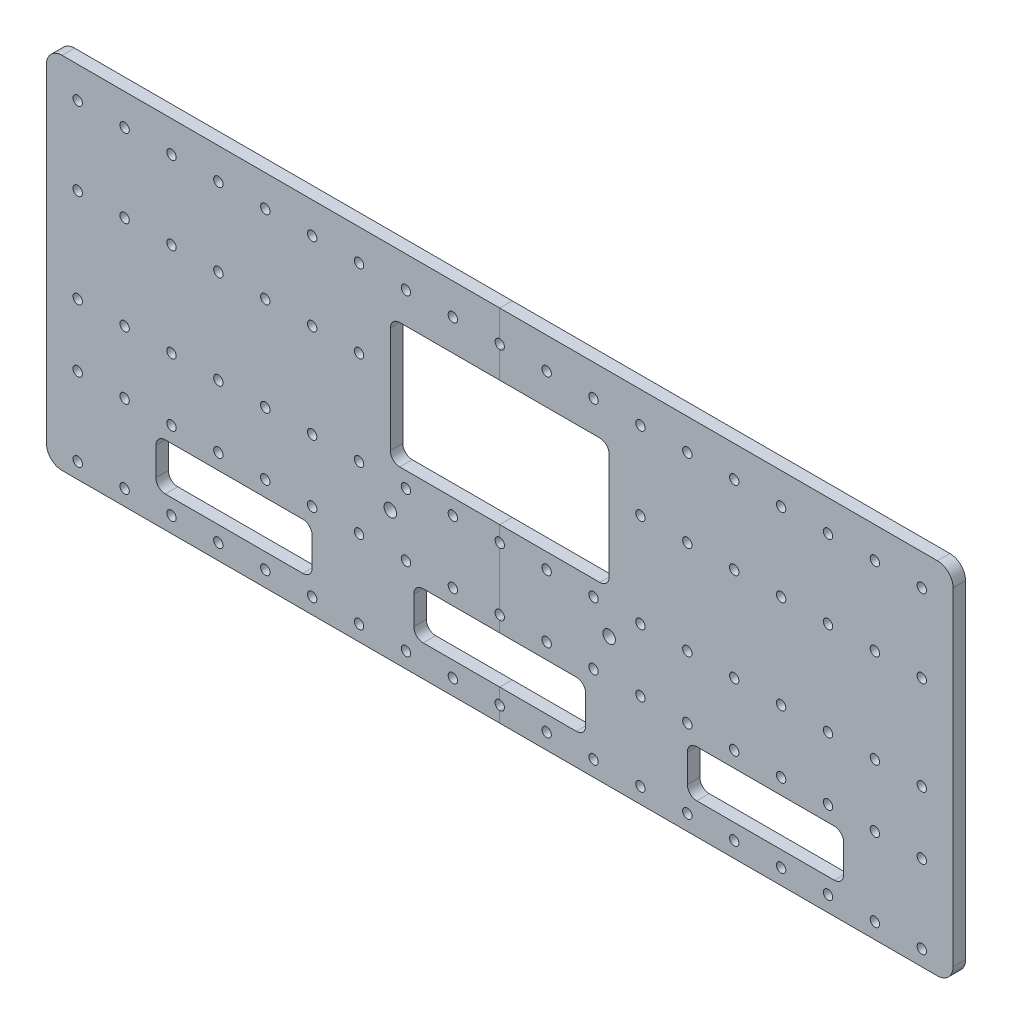
SolidWorks part; units mm, degrees
ref_plane "前视基准面" through (0, 0, 0) normal (0, 0, 1) x (1, 0, 0)
ref_plane "上视基准面" through (0, 0, 0) normal (0, 1, 0) x (1, 0, 0)
ref_plane "右视基准面" through (0, 0, 0) normal (1, 0, 0) x (0, 0, -1)
other "Configuration Table"
sketch "草图1" plane through (0, 0, 0) normal (0, 0, 1) x (1, 0, 0)
  line L1 (-145, 57.5) -> (145, 57.5)
  line L2 (-145, 57.5) -> (-145, -57.5)
  line L3 (-145, -57.5) -> (145, -57.5)
  line L4 (145, 57.5) -> (145, -57.5)
  line L5 (-145, 57.5) -> (145, -57.5) construction
  line L6 (-145, -57.5) -> (145, 57.5) construction
  point P0 (0, 0)
  dimension "D1" = 290
  dimension "D2" = 115
extrude "凸台-拉伸1" add sketch "草图1" along normal blind 4
sketch "草图2" plane through (0, 0, 4) normal (0, 0, 1) x (1, 0, 0)
  line L0 (-145, 47.5) -> (49855, 47.5) construction
  line L1 (-145, -57.5) -> (145, -57.5) construction
  line L2 (-145, -40) -> (49855, -40) construction
  line L3 (-145, 57.5) -> (-145, -57.5) construction
  line L4 (0, 0) -> (0, -50000) construction
  line L5 (145, 57.5) -> (-145, 57.5) construction
  line L6 (-135, 47.5) -> (-120, 47.5) construction
  line L7 (-135, -27.5) -> (-120, -27.5) construction
  circle A1 centre (-135, 47.5) radius 1.5
  circle A2 centre (-120, 47.5) radius 1.5
  circle A3 centre (-105, 47.5) radius 1.5
  circle A4 centre (-90, 47.5) radius 1.5
  circle A5 centre (-75, 47.5) radius 1.5
  circle A6 centre (-60, 47.5) radius 1.5
  circle A7 centre (-45, 47.5) radius 1.5
  circle A8 centre (-30, 47.5) radius 1.5
  circle A9 centre (-15, 47.5) radius 1.5
  circle A10 centre (0, 47.5) radius 1.5
  circle A11 centre (15, 47.5) radius 1.5
  circle A12 centre (30, 47.5) radius 1.5
  circle A13 centre (45, 47.5) radius 1.5
  circle A14 centre (60, 47.5) radius 1.5
  circle A15 centre (75, 47.5) radius 1.5
  circle A16 centre (90, 47.5) radius 1.5
  circle A17 centre (105, 47.5) radius 1.5
  circle A18 centre (120, 47.5) radius 1.5
  circle A19 centre (135, 47.5) radius 1.5
  circle A21 centre (150, 47.5) radius 1.5 [skipped]
  circle A22 centre (-135, -27.5) radius 1.5
  circle A23 centre (-120, -27.5) radius 1.5
  circle A24 centre (-105, -27.5) radius 1.5
  circle A25 centre (-90, -27.5) radius 1.5
  circle A26 centre (-75, -27.5) radius 1.5
  circle A27 centre (-60, -27.5) radius 1.5
  circle A28 centre (-45, -27.5) radius 1.5
  circle A29 centre (-30, -27.5) radius 1.5
  circle A30 centre (-15, -27.5) radius 1.5
  circle A31 centre (0, -27.5) radius 1.5
  circle A32 centre (15, -27.5) radius 1.5
  circle A33 centre (30, -27.5) radius 1.5
  circle A34 centre (45, -27.5) radius 1.5
  circle A35 centre (60, -27.5) radius 1.5
  circle A36 centre (75, -27.5) radius 1.5
  circle A37 centre (90, -27.5) radius 1.5
  circle A38 centre (105, -27.5) radius 1.5
  circle A39 centre (120, -27.5) radius 1.5
  circle A40 centre (135, -27.5) radius 1.5
  circle A50 centre (150, -27.5) radius 1.5 [skipped]
  circle A51 centre (165, -27.5) radius 1.5 [skipped]
  circle A52 centre (180, -27.5) radius 1.5 [skipped]
  circle A53 centre (195, -27.5) radius 1.5 [skipped]
  circle A54 centre (210, -27.5) radius 1.5 [skipped]
  circle A55 centre (225, -27.5) radius 1.5 [skipped]
  circle A56 centre (240, -27.5) radius 1.5 [skipped]
  circle A57 centre (255, -27.5) radius 1.5 [skipped]
  circle A58 centre (270, -27.5) radius 1.5 [skipped]
  circle A59 centre (135, -52.5) radius 1.5
  circle A60 centre (120, -52.5) radius 1.5
  circle A61 centre (105, -52.5) radius 1.5
  circle A62 centre (90, -52.5) radius 1.5
  circle A63 centre (75, -52.5) radius 1.5
  circle A64 centre (60, -52.5) radius 1.5
  circle A65 centre (45, -52.5) radius 1.5
  circle A66 centre (30, -52.5) radius 1.5
  circle A67 centre (15, -52.5) radius 1.5
  circle A68 centre (0, -52.5) radius 1.5
  circle A69 centre (-15, -52.5) radius 1.5
  circle A70 centre (-30, -52.5) radius 1.5
  circle A71 centre (-45, -52.5) radius 1.5
  circle A72 centre (-60, -52.5) radius 1.5
  circle A73 centre (-75, -52.5) radius 1.5
  circle A74 centre (-90, -52.5) radius 1.5
  circle A75 centre (-105, -52.5) radius 1.5
  circle A76 centre (-120, -52.5) radius 1.5
  circle A77 centre (-135, -52.5) radius 1.5
  dimension "D4" = 3
  dimension "D6" = 10
  dimension "D9" = 25
  dimension "D10" = 3
  dimension "D1" = 10
  dimension "D3" = 15
  dimension "D5" = 17.5
  dimension "D8" = 15
  dimension "D2" = 20
  dimension "D7" = 28
extrude "切除-拉伸1" cut sketch "草图2" against normal through all
sketch "草图3" plane through (0, 0, 4) normal (0, 0, 1) x (1, 0, 0)
  line L0 (0, 0) -> (0, -50000) construction
  line L1 (0, -16) -> (50000, -16) construction
  line L2 (-145, -57.5) -> (145, -57.5) construction
  circle A0 centre (-35, -16) radius 2
  circle A1 centre (35, -16) radius 2
  dimension "D2" = 4
  dimension "D3" = 70
  dimension "D1" = 41.5
extrude "切除-拉伸2" cut sketch "草图3" against normal through all
sketch "草图4" plane through (0, 0, 4) normal (0, 0, 1) x (1, 0, 0)
  line L0 (0, 0) -> (0, -50000) construction
  line L1 (145, -40) -> (-49855, -40) construction
  line L3 (-145, -57.5) -> (145, -57.5) construction
  line L5 (-27.5, -32.5) -> (27.5, -32.5)
  line L6 (-27.5, -32.5) -> (-27.5, -47.5)
  line L7 (-27.5, -47.5) -> (27.5, -47.5)
  line L8 (27.5, -32.5) -> (27.5, -47.5)
  line L9 (-27.5, -32.5) -> (27.5, -47.5) construction
  line L10 (-27.5, -47.5) -> (27.5, -32.5) construction
  point P7 (0, -40)
  dimension "D1" = 17.5
  dimension "D2" = 15
  dimension "D3" = 55
extrude "切除-拉伸3" cut sketch "草图4" against normal through all
sketch "草图5" plane through (0, 0, 4) normal (0, 0, 1) x (1, 0, 0)
  line L0 (-135, -7.5) -> (-120, -7.5) construction
  line L1 (-145, -57.5) -> (145, -57.5) construction
  line L2 (-135, 47.5) -> (-135, -49952.5) construction
  circle A0 centre (-135, -7.5) radius 1.5
  circle A1 centre (-120, -7.5) radius 1.5
  circle A2 centre (-105, -7.5) radius 1.5
  circle A3 centre (-90, -7.5) radius 1.5
  circle A4 centre (-75, -7.5) radius 1.5
  circle A5 centre (-60, -7.5) radius 1.5
  circle A6 centre (-45, -7.5) radius 1.5
  circle A7 centre (-30, -7.5) radius 1.5
  circle A8 centre (-15, -7.5) radius 1.5
  circle A9 centre (0, -7.5) radius 1.5
  circle A10 centre (15, -7.5) radius 1.5
  circle A11 centre (30, -7.5) radius 1.5
  circle A12 centre (45, -7.5) radius 1.5
  circle A13 centre (60, -7.5) radius 1.5
  circle A14 centre (75, -7.5) radius 1.5
  circle A15 centre (90, -7.5) radius 1.5
  circle A16 centre (105, -7.5) radius 1.5
  circle A17 centre (120, -7.5) radius 1.5
  circle A18 centre (135, -7.5) radius 1.5
  circle A19 centre (150, -7.5) radius 1.5
  circle A20 centre (-120, 22.5) radius 1.5
  circle A21 centre (-105, 22.5) radius 1.5
  circle A22 centre (-90, 22.5) radius 1.5
  circle A23 centre (-75, 22.5) radius 1.5
  circle A24 centre (-60, 22.5) radius 1.5
  circle A25 centre (-45, 22.5) radius 1.5
  circle A26 centre (-30, 22.5) radius 1.5
  circle A27 centre (-15, 22.5) radius 1.5
  circle A28 centre (0, 22.5) radius 1.5
  circle A29 centre (15, 22.5) radius 1.5
  circle A30 centre (30, 22.5) radius 1.5
  circle A31 centre (45, 22.5) radius 1.5
  circle A32 centre (60, 22.5) radius 1.5
  circle A33 centre (75, 22.5) radius 1.5
  circle A34 centre (90, 22.5) radius 1.5
  circle A35 centre (105, 22.5) radius 1.5
  circle A36 centre (120, 22.5) radius 1.5
  circle A37 centre (135, 22.5) radius 1.5
  circle A38 centre (150, 22.5) radius 1.5
  circle A39 centre (-135, 22.5) radius 1.5
  dimension "D4" = 50
  dimension "D5" = 3
  dimension "D6" = 30
  dimension "D3" = 15
  dimension "D1" = 20
  dimension "D2" = 2
extrude "切除-拉伸4" cut sketch "草图5" against normal through all
fillet "圆角1" radius 3 4 edges at (27.5, -47.5, 2) (27.5, -32.5, 2) (-27.5, -32.5, 2) (-27.5, -47.5, 2)
sketch "草图6" plane through (0, 0, 4) normal (0, 0, 1) x (1, 0, 0)
  line L0 (0, 0) -> (0, -50000) construction
  line L1 (145, 57.5) -> (-145, 57.5) construction
  line L2 (-32, 37.5) -> (32, 37.5)
  line L3 (-35, 34.5) -> (-35, 0.5)
  line L4 (-32, -2.5) -> (32, -2.5)
  line L5 (35, 34.5) -> (35, 0.5)
  line L6 (-35, 37.5) -> (35, -2.5) construction
  line L7 (-35, -2.5) -> (35, 37.5) construction
  line L8 (-145, -57.5) -> (145, -57.5) construction
  line L9 (-85, -53.1738) -> (-85, -50053.1738) construction
  line L10 (24.5, -32.5) -> (-24.5, -32.5) construction
  line L11 (-107, -32.5) -> (-63, -32.5)
  line L12 (-110, -35.5) -> (-110, -44.5)
  line L13 (-107, -47.5) -> (-63, -47.5)
  line L14 (-60, -35.5) -> (-60, -44.5)
  line L15 (-110, -32.5) -> (-60, -47.5) construction
  line L16 (-110, -47.5) -> (-60, -32.5) construction
  line L17 (-24.5, -47.5) -> (24.5, -47.5) construction
  line L18 (107, -47.5) -> (63, -47.5)
  line L19 (60, -35.5) -> (60, -44.5)
  line L20 (107, -32.5) -> (63, -32.5)
  line L21 (110, -35.5) -> (110, -44.5)
  arc A0 (32, -2.5) -> (35, 0.5) centre (32, 0.5) ccw
  arc A1 (32, 37.5) -> (35, 34.5) centre (32, 34.5) cw
  arc A2 (-35, 0.5) -> (-32, -2.5) centre (-32, 0.5) ccw
  arc A3 (-32, 37.5) -> (-35, 34.5) centre (-32, 34.5) ccw
  arc A4 (-63, -32.5) -> (-60, -35.5) centre (-63, -35.5) cw
  arc A5 (-63, -47.5) -> (-60, -44.5) centre (-63, -44.5) ccw
  arc A6 (-110, -44.5) -> (-107, -47.5) centre (-107, -44.5) ccw
  arc A7 (-107, -32.5) -> (-110, -35.5) centre (-107, -35.5) ccw
  arc A8 (63, -47.5) -> (60, -44.5) centre (63, -44.5) cw
  arc A9 (63, -32.5) -> (60, -35.5) centre (63, -35.5) ccw
  arc A10 (110, -44.5) -> (107, -47.5) centre (107, -44.5) cw
  arc A11 (107, -32.5) -> (110, -35.5) centre (107, -35.5) cw
  point P3 (0, 17.5)
  point P14 (-85, -40)
  dimension "D6" = 3
  dimension "D1" = 20
  dimension "D2" = 55
  dimension "D3" = 70
  dimension "D4" = 85
  dimension "D5" = 50
extrude "切除-拉伸5" cut sketch "草图6" against normal through all
fillet "圆角2" radius 5 4 edges at (145, -57.5, 2) (145, 57.5, 2) (-145, -57.5, 2) (-145, 57.5, 2)
ref_plane "基准面1" through (0, 0, 0) normal (-1, 0, 0) x (0, 0, 1)
split "分割1" trim tools "基准面1" bodies to split 111 resulting bodies 112 113
